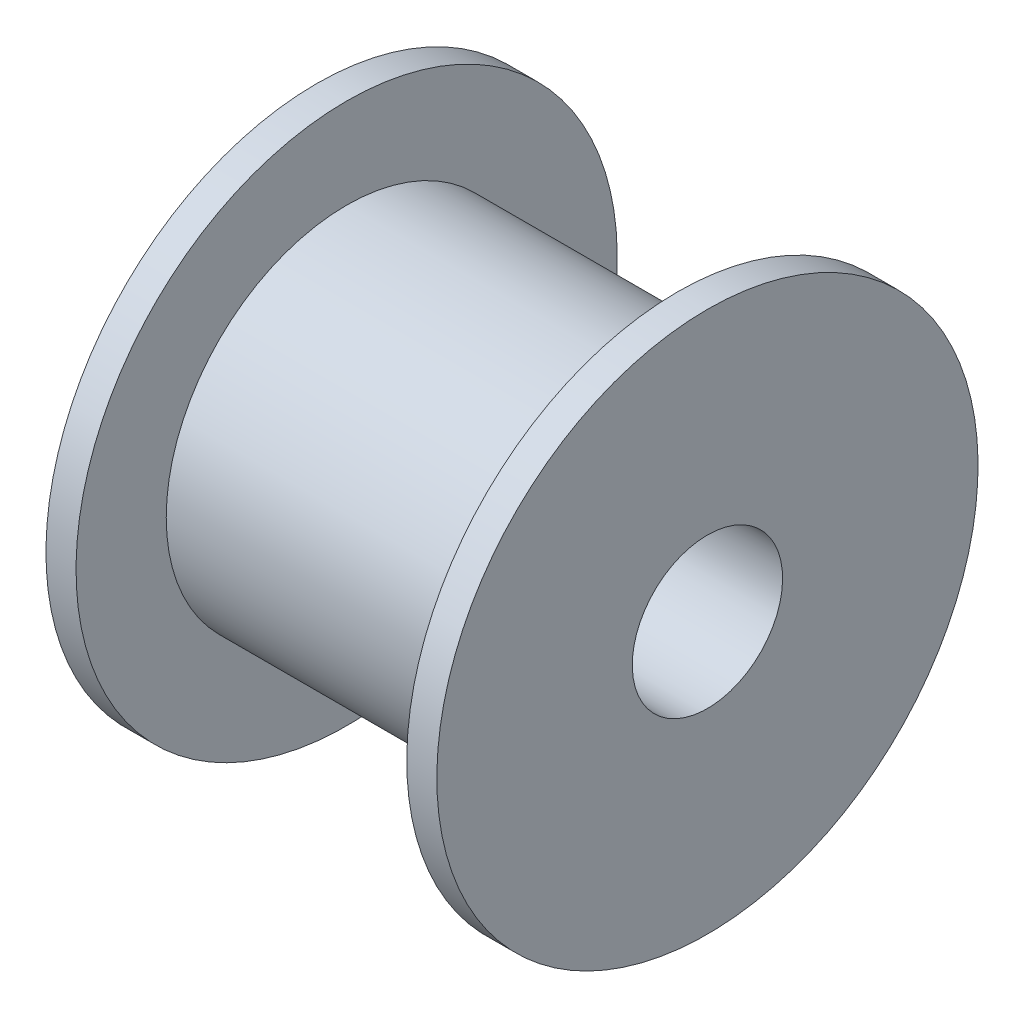
SolidWorks part; units mm, degrees
ref_plane "Front" through (0, 0, 0) normal (0, 0, 1) x (1, 0, 0)
ref_plane "Top" through (0, 0, 0) normal (0, 1, 0) x (1, 0, 0)
ref_plane "Right" through (0, 0, 0) normal (1, 0, 0) x (0, 0, -1)
sketch "Эскиз2" plane through (0, 0, 0) normal (0, 0, 1) x (1, 0, 0)
  line L0 (0, 0) -> (-13, 0)
  line L1 (-13, 0) -> (-13, 9)
  line L2 (-13, 9) -> (-12, 9)
  line L3 (0, 9) -> (0, 0)
  line L4 (-13, 9) -> (-12, 9)
  line L5 (-12, 9) -> (-12, 6)
  line L6 (-12, 6) -> (-1, 6)
  line L7 (-1, 6) -> (-1, 9)
  line L8 (-1, 9) -> (0, 9)
  line L9 (-13, 2.5) -> (0, 2.5)
revolve "Повернуть1" add sketch "Эскиз2" angle 360 about L0
